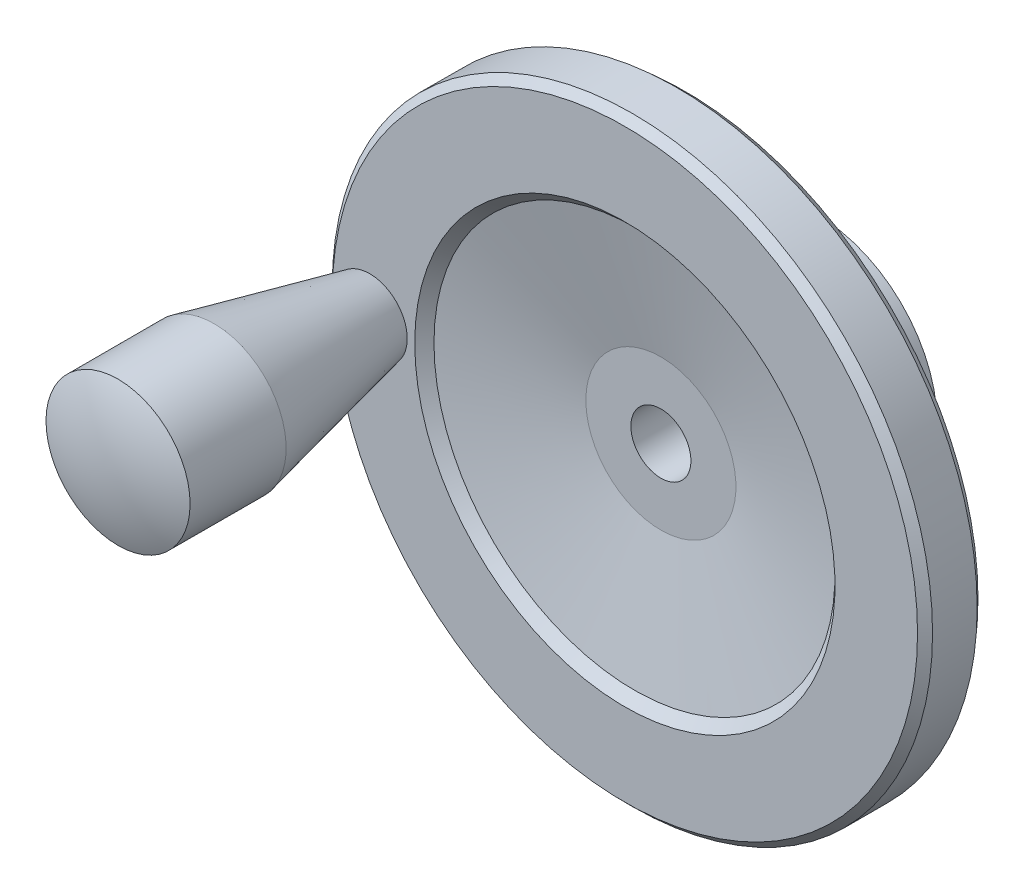
SolidWorks part; units mm, degrees
ref_plane "Front Plane" through (0, 0, 0) normal (0, 0, 1) x (1, 0, 0)
ref_plane "Top Plane" through (0, 0, 0) normal (0, 1, 0) x (1, 0, 0)
ref_plane "Right Plane" through (0, 0, 0) normal (1, 0, 0) x (0, 0, -1)
sketch "Sketch1" plane through (0, 0, 0) normal (0, 0, 1) x (1, 0, 0)
  circle A0 centre (0, 0) radius 31.75
  dimension "D1" = 63.5
extrude "Extrude1" add sketch "Sketch1" along normal blind 6.35
sketch "Sketch2" plane through (0, 0, 0) normal (0, 1, 0) x (1, 0, 0)
  line L0 (22.225, -6.35) -> (21.209, -5.334)
  line L1 (-31.75, -6.35) -> (31.75, -6.35) construction
  line L2 (21.209, -5.334) -> (7.9375, -2.54)
  line L3 (7.9375, -2.54) -> (0, -2.54)
  line L4 (0, 0) -> (0, -6.35) construction
  line L5 (-21.209, -5.334) -> (-7.9375, -2.54) construction
  line L6 (-22.225, -6.35) -> (-21.209, -5.334) construction
  line L7 (0, -6.35) -> (22.225, -6.35)
  line L8 (0, -2.54) -> (-7.9375, -2.54) construction
  line L9 (0, -6.35) -> (-22.225, -6.35) construction
  line L10 (0, -6.35) -> (0, -2.54)
  point P10 (0, -2.54)
  dimension "D1" = 3.81
  dimension "D2" = 1.016
  dimension "D3" = 1.016
  dimension "D4" = 15.875
  dimension "D5" = 44.45
revolve "Cut-Revolve4" cut sketch "Sketch2" angle 360 about L4
sketch "Sketch3" plane through (0, 0, 0) normal (0, 1, 0) x (1, 0, 0)
  line L0 (-31.75, 0) -> (-7.9375, 1.27)
  line L1 (0, 0) -> (0, 15.3458) construction
  line L2 (-7.9375, 1.27) -> (0, 1.27)
  line L3 (-31.75, 0) -> (0, 0)
  line L4 (0, 1.27) -> (0, 0)
  line L5 (31.75, 0) -> (7.9375, 1.27) construction
  line L6 (7.9375, 1.27) -> (0, 1.27) construction
  line L7 (31.75, 0) -> (0, 0) construction
  dimension "D1" = 1.27
  dimension "D2" = 15.875
revolve "Revolve1" add sketch "Sketch3" angle 360 about L1
sketch "Sketch4" plane through (0, 0, -1.27) normal (0, 0, -1) x (-1, 0, 0)
  circle A1 centre (0, 0) radius 7.9375
  circle A2 centre (0, 0) radius 7.9375
  dimension "D1" = 0
extrude "Extrude2" add sketch "Sketch4" along normal blind 6.35
sketch "Sketch5" plane through (0, 0, -7.62) normal (0, 0, -1) x (-1, 0, 0)
  circle A0 centre (0, 0) radius 12.7
  circle A1 centre (0, 0) radius 7.9375 construction
  dimension "D1" = 25.4
extrude "Extrude3" add sketch "Sketch5" along normal offset from surface (6.35 mm away) 20.32 up to face at (31.75, 0, 6.35)
sketch "Sketch6" plane through (0, 0, -13.97) normal (0, 0, -1) x (-1, 0, 0)
  circle A0 centre (0, 0) radius 8.255
  dimension "D1" = 16.51
extrude "Extrude4" add sketch "Sketch6" along normal blind 0.254
sketch "Sketch7" plane through (0, 0, -14.224) normal (0, 0, -1) x (-1, 0, 0)
  circle A0 centre (0, 0) radius 3.175
  dimension "D1" = 6.35
extrude "Extrude5" cut sketch "Sketch7" against normal through all
fillet "Fillet1" radius 0.7937 1 edges at (-12.7, 0, -7.62)
chamfer "Chamfer1" distance 0.7937 angle 45 2 edges at (31.75, 0, 0) (31.75, 0, 6.35)
ref_plane "Plane1" through (-7.9375, 0, -4.445) normal (-1, 0, 0) x (0, -1, 0)
hole_wizard "#10-32 Tapped Hole1" positions "Sketch11" profile "Sketch10" tap size "#10-32" standard "Ansi Inch"
sketch "Sketch11" plane through (-7.9375, 0, -4.445) normal (-1, 0, 0) x (0, -1, 0)
  line L0 (0, -9.525) -> (0, -3.9687) construction
  line L1 (30.9563, 10.795) -> (-30.9563, 10.795) construction
  point P0 (0, 0.635)
  dimension "D1" = 10.16
sketch "Sketch10" plane through (-7.9375, 0, -3.81) normal (0, 1, 0) x (0, 0, 1)
  line L0 (0, 0) -> (0, 4.7625)
  line L1 (0, 4.7625) -> (2.0193, 4.7625)
  line L2 (2.0193, 4.7625) -> (2.0193, 0)
  line L5 (2.0193, 0) -> (0, 0)
  line L11 (0, -6.35) -> (0, 107.95) construction
  dimension "Thru Tap Drill Dia." = 4.0386
  dimension "Thru Tap Drill Depth" = 4.7625
cosmetic thread "Hole Thread1" parameters "D2"=4.826
sketch "Sketch12" plane through (0, 0, 6.35) normal (0, 0, 1) x (1, 0, 0)
  circle A0 centre (-26.9875, 0) radius 3.175
  circle A1 centre (0, 0) radius 26.9875 construction
  dimension "D1" = 53.975
  dimension "D2" = 6.35
extrude "Extrude6" add sketch "Sketch12" along normal blind 27.94
sketch "Sketch13" plane through (0, 0, 0) normal (0, 1, 0) x (1, 0, 0)
  line L0 (-26.9875, 6.6309) -> (-26.9875, -38.763) construction
  line L1 (-26.9875, -34.29) -> (-26.9875, -6.35) construction
  line L2 (-26.9875, -6.35) -> (-23.0187, -6.35)
  line L3 (-30.9563, -6.35) -> (30.9563, -6.35) construction
  line L4 (-23.0187, -6.35) -> (-19.3675, -22.8085)
  line L5 (-19.3675, -22.8085) -> (-19.3675, -32.9685)
  line L6 (-34.6075, -22.8085) -> (-34.6075, -32.9685) construction
  line L7 (-30.9562, -6.35) -> (-34.6075, -22.8085) construction
  line L8 (-26.9875, -34.556) -> (-26.9875, -6.35)
  arc A0 (-19.3675, -32.9685) -> (-26.9875, -34.556) centre (-26.9875, -15.4742) cw
  arc A1 (-26.9875, -34.556) -> (-34.6075, -32.9685) centre (-26.9875, -15.4742) cw construction
  dimension "D1" = 15.24
  dimension "D2" = 1.5875
  dimension "D3" = 7.9375
  dimension "D4" = 10.16
revolve "Revolve2" add sketch "Sketch13" angle 360 about L0
